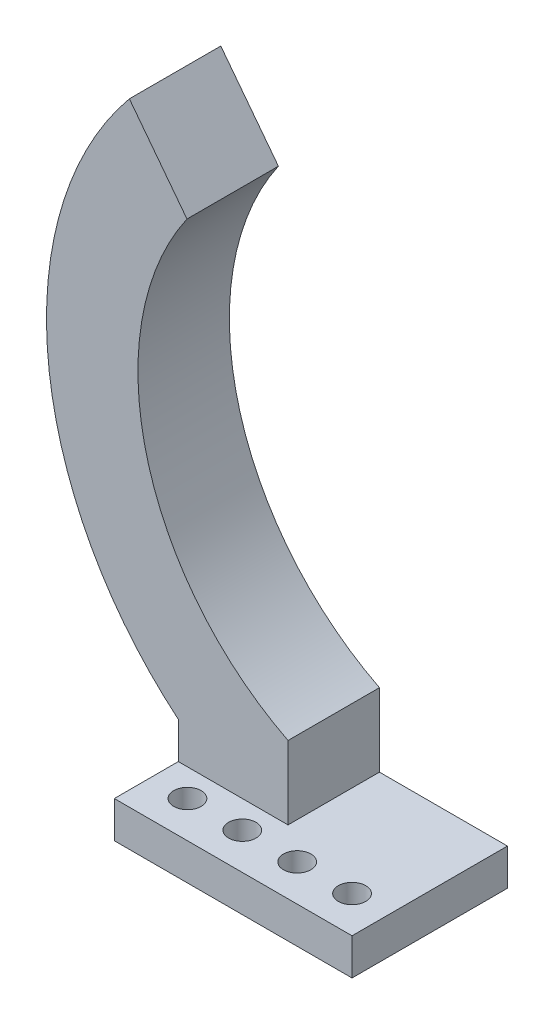
SolidWorks part; units mm, degrees
ref_plane "Front Plane" through (0, 0, 0) normal (0, 0, 1) x (1, 0, 0)
ref_plane "Top Plane" through (0, 0, 0) normal (0, 1, 0) x (1, 0, 0)
ref_plane "Right Plane" through (0, 0, 0) normal (1, 0, 0) x (0, 0, -1)
sketch "Sketch1" plane through (0, 0, 0) normal (0, 0, 1) x (1, 0, 0)
  line L28 (-5.354, 64.1029) -> (0.9478, 55.8676)
  line L31 (12, 12) -> (12, 4)
  line L32 (0, 0) -> (27, 0)
  line L35 (27, 0) -> (27, 4)
  line L39 (0, 8) -> (0, 4)
  line L40 (0, 4) -> (12, 4)
  line L43 (0, 0) -> (0, 4)
  line L44 (0, 4) -> (27, 4)
  arc A4 (0.9478, 55.8676) -> (12, 12) centre (25.5839, 38.7484) ccw
  arc A5 (-5.354, 64.1029) -> (0, 8) centre (25.5839, 38.7484) ccw
  point P0 (0.9226, 55.8313)
  dimension "D3" = 8
  dimension "D4" = 12
  dimension "D5" = 30
  dimension "D1" = 40
  dimension "D2" = 4
  dimension "D6" = 27
  dimension "D7" = 4
extrude "Boss-Extrude1" add sketch "Sketch1" along normal blind 10
sketch "Sketch3" plane through (0, 0, 0) normal (0, 0, 1) x (1, 0, 0)
  line L0 (0, 4) -> (26, 4)
  line L2 (0, 0) -> (0, 4)
  line L5 (26, 4) -> (26, 0)
  line L6 (26, 0) -> (0, 0)
  dimension "D1" = 26
extrude "Boss-Extrude2" add sketch "Sketch3" along normal blind 17 contours L6 L2 L0 L5
ref_plane "Plane1" through (0, 4, 0) normal (0, 1, 0) x (1, 0, 0)
sketch "Sketch4" plane through (0, 4, 0) normal (0, 1, 0) x (1, 0, 0)
  line L0 (26, -17) -> (0, -17) construction
  line L5 (26, -17) -> (26, 0) construction
  circle A0 centre (4, -13) radius 1.5
  circle A1 centre (10, -13) radius 1.5
  circle A2 centre (16, -13) radius 1.5
  circle A3 centre (22, -13) radius 1.5
  dimension "D1" = 6
  dimension "D2" = 6
  dimension "D3" = 6
  dimension "D4" = 4
  dimension "D5" = 4
extrude "Cut-Extrude1" cut sketch "Sketch4" against normal blind 4 contours A0 | A1 | A2 | A3
